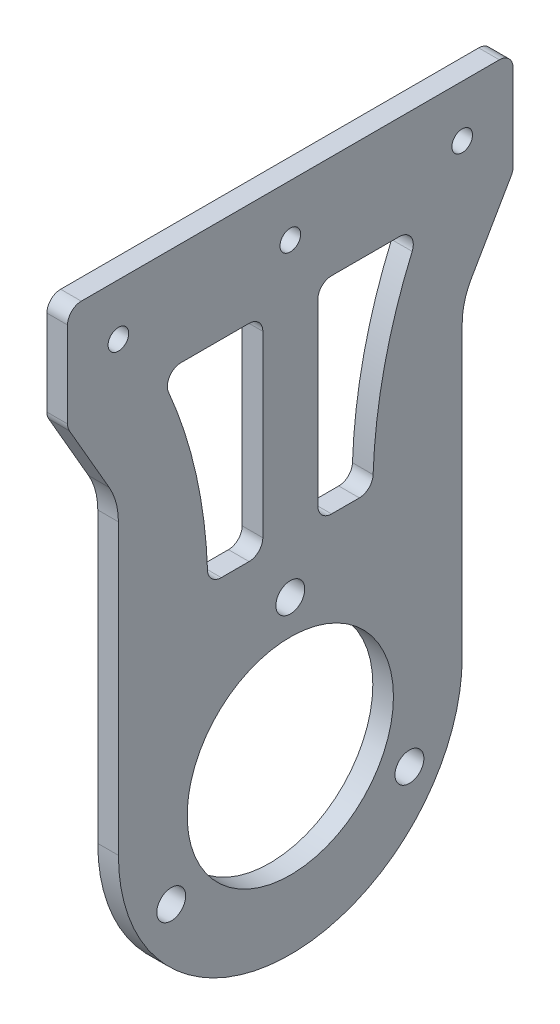
SolidWorks part; units mm, degrees
material "Thornel Mat VMA"
ref_plane "前视基准面" through (0, 0, 0) normal (0, 0, 1) x (1, 0, 0)
ref_plane "上视基准面" through (0, 0, 0) normal (0, 1, 0) x (1, 0, 0)
ref_plane "右视基准面" through (0, 0, 0) normal (1, 0, 0) x (0, 0, -1)
sketch "草图1" plane through (0, 0, 0) normal (1, 0, 0) x (0, 0, -1)
  line L0 (0, 0) -> (0, 65) construction
  line L1 (-25, 65) -> (25, 65) construction
  line L2 (-32.4, 72.5) -> (32.4, 72.5)
  line L3 (32.4, 72.5) -> (32.4, 57.5)
  line L4 (-19, 57.5) -> (-4, 57.5)
  line L5 (25, 44.6828) -> (25, 0)
  line L6 (-32.4, 72.5) -> (-32.4, 57.5)
  line L7 (-4, 57.5) -> (-4, 27.5)
  line L8 (-25, 44.6828) -> (-25, 0)
  line L9 (32.4, 57.5) -> (25, 44.6828)
  line L10 (-32.4, 57.5) -> (-25, 44.6828)
  line L11 (-4, 27.5) -> (-12, 27.5)
  line L12 (4, 27.5) -> (12, 27.5)
  line L13 (4, 57.5) -> (4, 27.5)
  line L14 (19, 57.5) -> (4, 57.5)
  circle A0 centre (0, 0) radius 15
  circle A1 centre (0, 20) radius 2.1
  circle A2 centre (17.3205, -10) radius 2.1
  circle A3 centre (-17.3205, -10) radius 2.1
  arc A4 (-19, 57.5) -> (-12, 27.5) centre (-81.9981, 26.9838) cw
  arc A5 (-25, 0) -> (25, 0) centre (0, 0) ccw
  circle A6 centre (-25, 65) radius 1.5
  circle A7 centre (0, 65) radius 1.5
  arc A8 (19, 57.5) -> (12, 27.5) centre (81.9981, 26.9838) ccw
  circle A9 centre (25, 65) radius 1.5
  point P12 (0, 0)
  point P13 (0, 0)
  point P25 (-17.3205, 57.5)
  point P28 (0, 65)
  point P30 (0, 72.5)
  dimension "D2" = 20
  dimension "D4" = 30
  dimension "D5" = 50
  dimension "D7" = 3
  dimension "D8" = 50
  dimension "D9" = 60
  dimension "D13" = 4.2
  dimension "D16" = 70
  dimension "D6" = 65
  dimension "D10" = 15
  dimension "D11" = 7.5
  dimension "D12" = 64.8
  dimension "D14" = 4
  dimension "D15" = 15
  dimension "D17" = 30
  dimension "D18" = 8
  dimension "D3" = 3
extrude "凸台-拉伸1" add sketch "草图1" along normal blind 3
fillet "圆角2" radius 2 12 edges at (1.5, 72.5, -32.4) (1.5, 72.5, 32.4) (1.5, 57.5, 32.4) (1.5, 57.5, -32.4) (1.5, 27.5, -12) (1.5, 27.5, 12) (1.5, 27.5, 4) (1.5, 27.5, -4) (1.5, 57.5, -4) (1.5, 57.5, 4) (1.5, 57.5, -19) (1.5, 57.5, 19)
fillet "圆角3" radius 10 2 edges at (1.5, 44.6828, -25) (1.5, 44.6828, 25)
